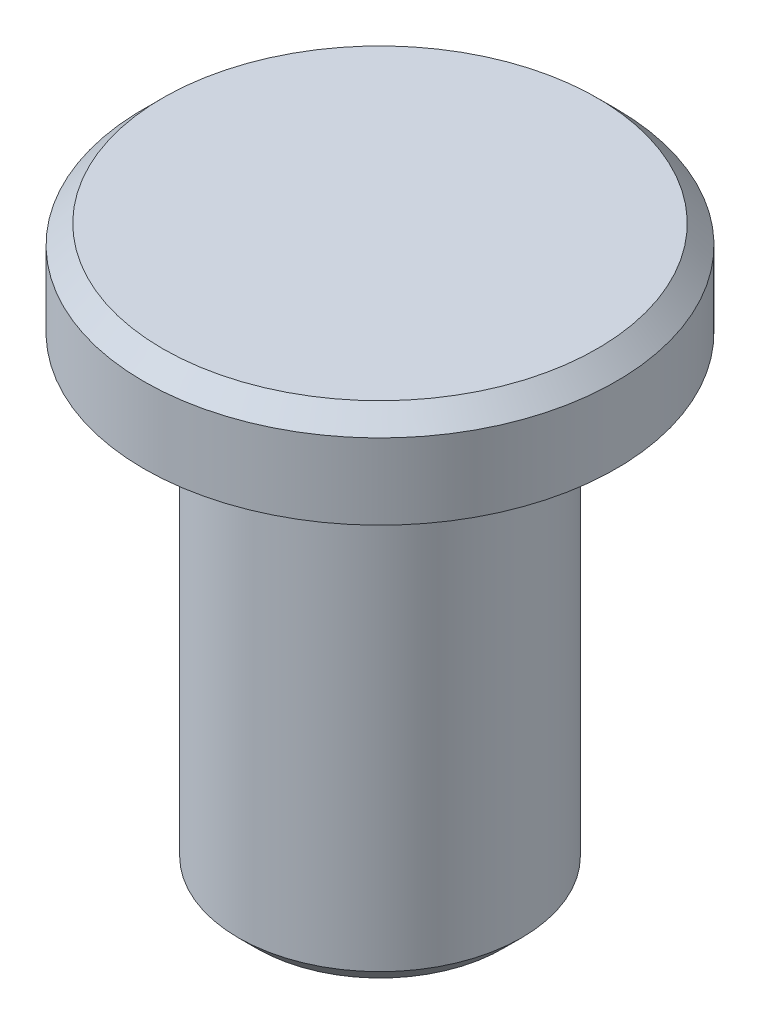
SolidWorks part; units mm, degrees
ref_plane "Front Plane" through (0, 0, 0) normal (0, 0, 1) x (1, 0, 0)
ref_plane "Top Plane" through (0, 0, 0) normal (0, 1, 0) x (1, 0, 0)
ref_plane "Right Plane" through (0, 0, 0) normal (1, 0, 0) x (0, 0, -1)
sketch "Sketch1" plane through (0, 0, 0) normal (0, 0, 1) x (1, 0, 0)
  line L0 (0, 0) -> (0, 6)
  line L1 (0, 6) -> (2.5, 6)
  line L2 (2.5, 6) -> (2.5, 5)
  line L3 (2.5, 5) -> (1.5, 5)
  line L4 (1.5, 5) -> (1.5, 0)
  line L5 (1.5, 0) -> (0, 0)
  dimension "D1" = 6
  dimension "D2" = 2.5
  dimension "D3" = 1.5
  dimension "D4" = 5
revolve "Revolve1" add sketch "Sketch1" angle 360 about L0
chamfer "Chamfer1" distance 0.2 angle 45 2 edges at (0, 0, -1.5) (0, 6, -2.5)
